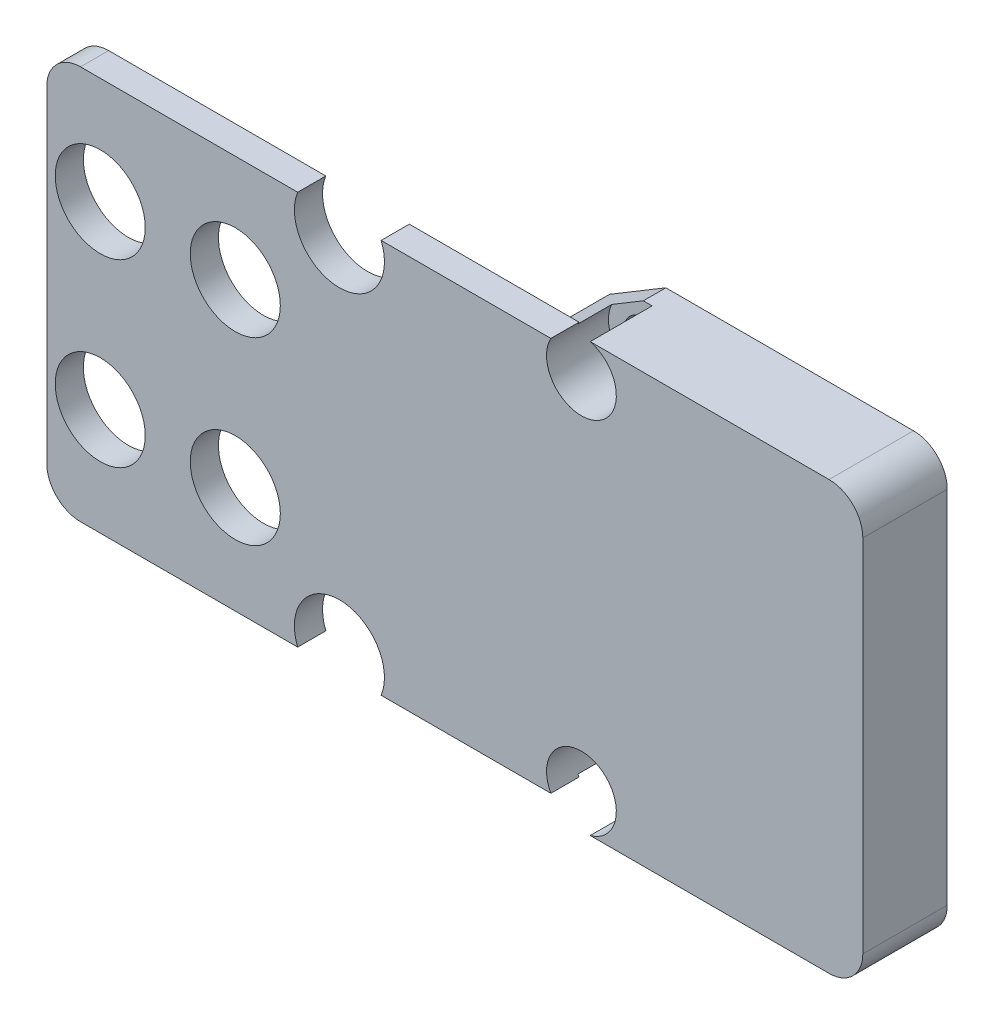
SolidWorks part; units mm, degrees
ref_plane "Alzado" through (0, 0, 0) normal (0, 0, 1) x (1, 0, 0)
ref_plane "Planta" through (0, 0, 0) normal (0, 1, 0) x (1, 0, 0)
ref_plane "Vista lateral" through (0, 0, 0) normal (1, 0, 0) x (0, 0, -1)
sketch "Croquis1" plane through (0, 0, 0) normal (0, 0, 1) x (1, 0, 0)
  line L0 (-69.5865, 30.6996) -> (-44.5865, 30.6996)
  line L1 (-69.5865, -7.3004) -> (-44.5865, -7.3004)
  line L2 (-44.5865, 30.6996) -> (-44.5865, -7.3004)
  line L3 (-69.5865, 27.6996) -> (-74.5865, 27.6996) construction
  line L4 (-74.5865, 27.6996) -> (-74.5865, -4.3004)
  line L5 (-74.5865, -4.3004) -> (-69.5865, -7.3004)
  line L6 (-74.5865, 27.6996) -> (-69.5865, 30.6996)
  circle A0 centre (-69.5865, 27.6996) radius 1.7074
  circle A1 centre (-69.5865, -4.3004) radius 1.7074
  dimension "D1" = 32
  dimension "D2" = 3
  dimension "D3" = 3
  dimension "D4" = 25
  dimension "D5" = 25
extrude "Saliente-Extruir1" add sketch "Croquis1" along normal blind 7.5
sketch "Croquis4" plane through (0, 0, 7.5) normal (0, 0, 1) x (1, 0, 0)
  line L0 (-72.0865, 29.1996) -> (-117.0865, 29.1996)
  line L1 (-69.5865, 30.6996) -> (-74.5865, 27.6996) construction
  line L2 (-117.0865, 29.1996) -> (-117.0865, -5.8004)
  line L3 (-117.0865, -5.8004) -> (-72.0865, -5.8004)
  line L4 (-74.5865, -4.3004) -> (-69.5865, -7.3004) construction
  line L5 (-72.0865, -5.8004) -> (-74.5865, -4.3004)
  line L6 (-74.5865, -4.3004) -> (-74.5865, 27.6996)
  line L7 (-74.5865, 27.6996) -> (-72.0865, 29.1996)
  dimension "D1" = 45
extrude "Saliente-Extruir2" add sketch "Croquis4" against normal blind 2.5
sketch "Croquis5" plane through (0, 0, 7.5) normal (0, 0, 1) x (1, 0, 0)
  line L0 (-69.5865, -4.3004) -> (-117.0865, -4.3004) construction
  line L1 (-117.0865, 29.1996) -> (-117.0865, -5.8004) construction
  line L2 (-69.5865, 27.6996) -> (-117.0865, 27.6996) construction
  line L3 (-121.5865, -4.3004) -> (-91.0865, 27.6996) construction
  line L4 (-91.0865, 27.6996) -> (-121.5865, 27.6996) construction
  line L5 (-121.5865, 27.6996) -> (-91.0865, -4.3004) construction
  line L11 (-112.3365, 19.6996) -> (-100.3365, 3.6996) construction
  line L12 (-112.3365, 3.6996) -> (-100.3365, 19.6996) construction
  circle A0 centre (-91.0865, -4.3004) radius 4
  circle A1 centre (-91.0865, 27.6996) radius 4
  circle A2 centre (-121.5865, -4.3004) radius 3.5
  circle A3 centre (-121.5865, 27.6996) radius 3.5
  circle A4 centre (-100.3365, 19.6996) radius 4
  circle A5 centre (-112.3365, 19.6996) radius 4
  circle A6 centre (-112.3365, 3.6996) radius 4
  circle A7 centre (-100.3365, 3.6996) radius 4
  point P16 (-106.3365, 11.6996)
  dimension "D1" = 21.5
  dimension "D2" = 30.5
  dimension "D3" = 16
  dimension "D5" = 7
  dimension "D6" = 8
  dimension "D7" = 7
  dimension "D8" = 8
  dimension "D9" = 8
  dimension "D10" = 8
  dimension "D11" = 8
  dimension "D12" = 8
  dimension "D4" = 12
extrude "Cortar-Extruir1" cut sketch "Croquis5" against normal up to vertex (2.5 mm away)
fillet "Redondeo1" radius 3 4 edges at (-117.0865, 29.1996, 6.25) (-117.0865, -5.8004, 6.25) (-44.5865, 30.6996, 3.75) (-44.5865, -7.3004, 3.75)
sketch "Croquis6" plane through (0, 0, 7.5) normal (0, 0, 1) x (1, 0, 0)
  circle A0 centre (-69.5865, 27.6996) radius 3.1
  circle A1 centre (-69.5865, -4.3004) radius 3.1
  dimension "D1" = 6.2
  dimension "D2" = 6.2
extrude "Cortar-Extruir2" cut sketch "Croquis6" against normal blind 5.5
